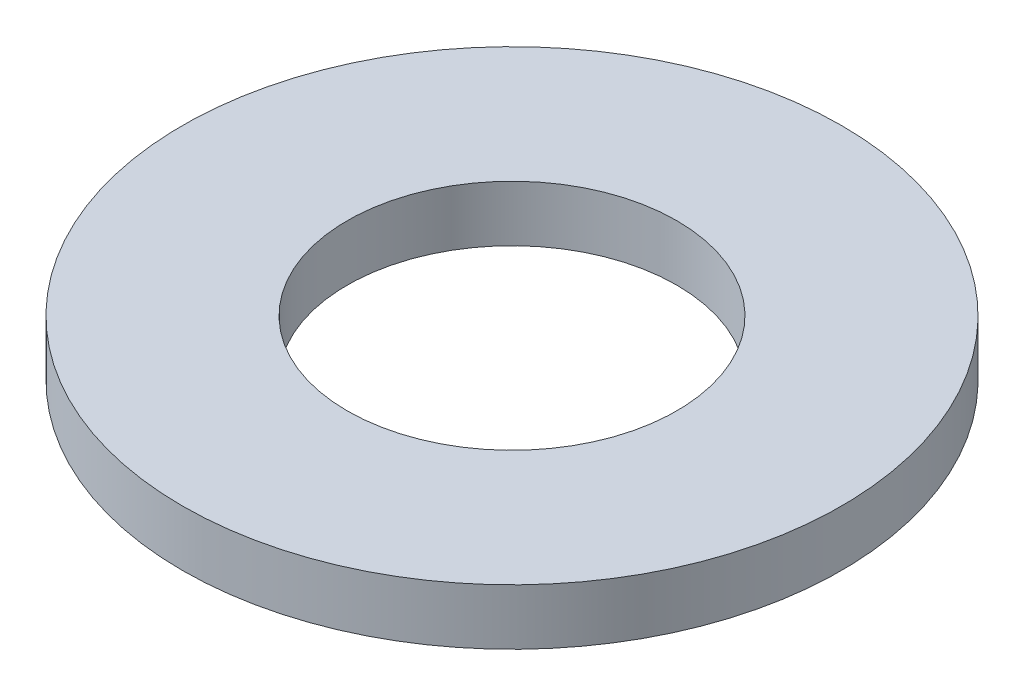
SolidWorks part; units mm, degrees
ref_plane "Спереди" through (0, 0, 0) normal (0, 0, 1) x (1, 0, 0)
ref_plane "Сверху" through (0, 0, 0) normal (0, 1, 0) x (1, 0, 0)
ref_plane "Справа" through (0, 0, 0) normal (1, 0, 0) x (0, 0, -1)
sketch "Эскиз1" plane through (0, 0, 0) normal (0, 1, 0) x (1, 0, 0)
  circle A0 centre (0, 0) radius 59
  circle A1 centre (0, 0) radius 29.5
extrude "Бобышка-Вытянуть1" add sketch "Эскиз1" along normal blind 10
